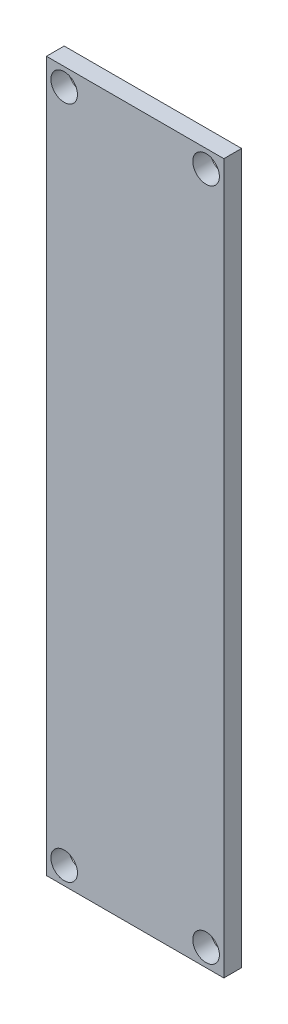
SolidWorks part; units mm, degrees
ref_plane "Front Plane" through (0, 0, 0) normal (0, 0, 1) x (1, 0, 0)
ref_plane "Top Plane" through (0, 0, 0) normal (0, 1, 0) x (1, 0, 0)
ref_plane "Right Plane" through (0, 0, 0) normal (1, 0, 0) x (0, 0, -1)
sketch "Sketch1" plane through (0, 0, 0) normal (0, 0, 1) x (1, 0, 0)
  line L1 (31.8075, -23.0628) -> (51.8075, -23.0628)
  line L2 (31.8075, -23.0628) -> (31.8075, -103.0628)
  line L3 (31.8075, -103.0628) -> (51.8075, -103.0628)
  line L4 (51.8075, -23.0628) -> (51.8075, -103.0628)
  dimension "D1" = 20
  dimension "D2" = 80
extrude "Boss-Extrude1" add sketch "Sketch1" along normal blind 2
sketch "Sketch2" plane through (0, 0, 2) normal (0, 0, 1) x (1, 0, 0)
  line L0 (41.4187, 352.3529) -> (41.4187, 432.3529) construction
  line L1 (31.8075, -25.0628) -> (33.8075, -25.0628) construction
  line L2 (31.8075, -23.0628) -> (31.8075, -103.0628) construction
  line L3 (33.8075, -25.0628) -> (33.8075, -23.0628) construction
  line L4 (51.8075, -23.0628) -> (31.8075, -23.0628) construction
  line L5 (41.8075, -23.0628) -> (41.8075, -103.0628) construction
  line L6 (31.8075, -103.0628) -> (51.8075, -103.0628) construction
  line L7 (41.8075, -63.0628) -> (31.8075, -63.0628) construction
  circle A0 centre (33.8075, -25.0628) radius 1.5
  circle A1 centre (49.8075, -25.0628) radius 1.5
  circle A2 centre (33.8075, -101.0628) radius 1.5
  circle A3 centre (49.8075, -101.0628) radius 1.5
  dimension "D1" = 80
  dimension "D2" = 2
  dimension "D3" = 2
extrude "Cut-Extrude1" cut sketch "Sketch2" against normal blind 2
